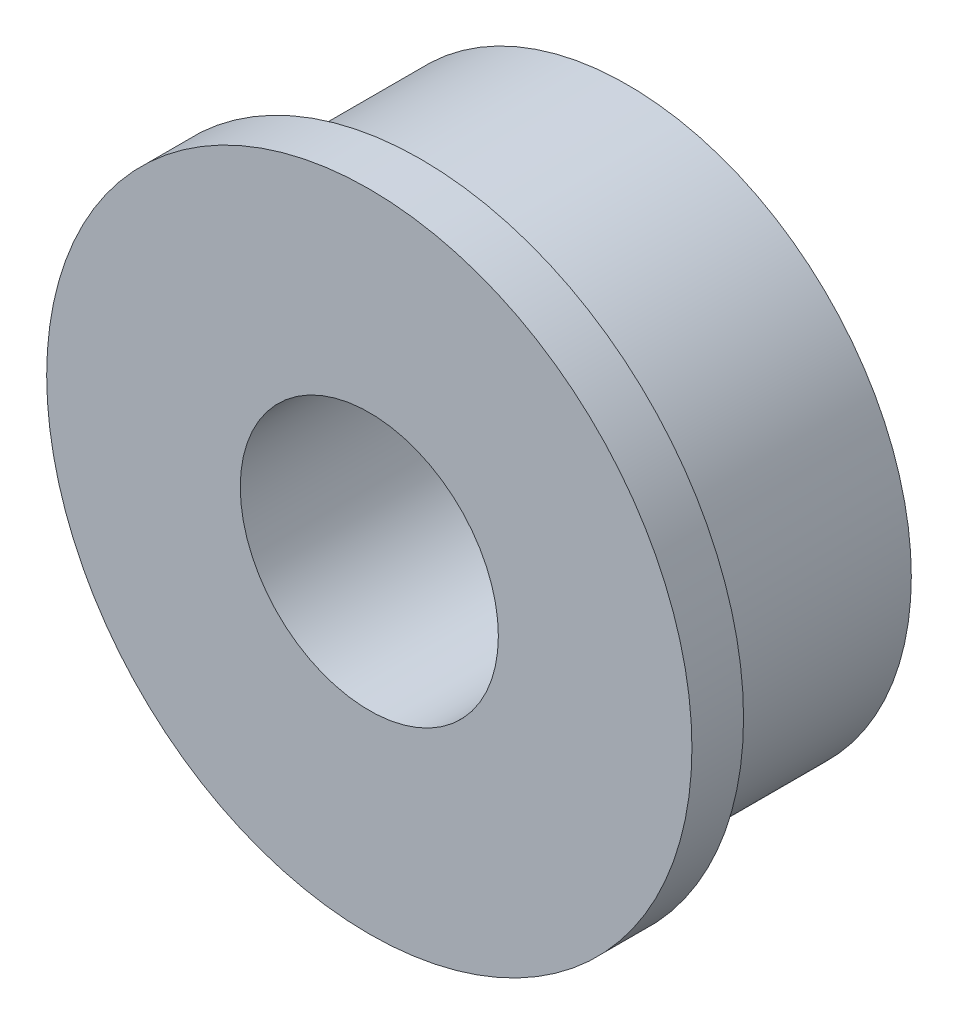
SolidWorks part; units mm, degrees
material "AISI 1045 钢，冷拔"
ref_plane "前视基准面" through (0, 0, 0) normal (0, 0, 1) x (1, 0, 0)
ref_plane "上视基准面" through (0, 0, 0) normal (0, 1, 0) x (1, 0, 0)
ref_plane "右视基准面" through (0, 0, 0) normal (1, 0, 0) x (0, 0, -1)
sketch "草图1" plane through (0, 0, 0) normal (0, 0, 1) x (1, 0, 0)
  circle A0 centre (0, 0) radius 5.5
  circle A1 centre (0, 0) radius 2.5
  dimension "D1" = 11
  dimension "D2" = 5
extrude "凸台-拉伸1" add sketch "草图1" along normal blind 4
sketch "草图2" plane through (0, 0, 4) normal (0, 0, 1) x (1, 0, 0)
  circle A0 centre (0, 0) radius 2.5
  circle A1 centre (0, 0) radius 6.25
  dimension "D1" = 12.5
extrude "凸台-拉伸2" add sketch "草图2" along normal blind 1
